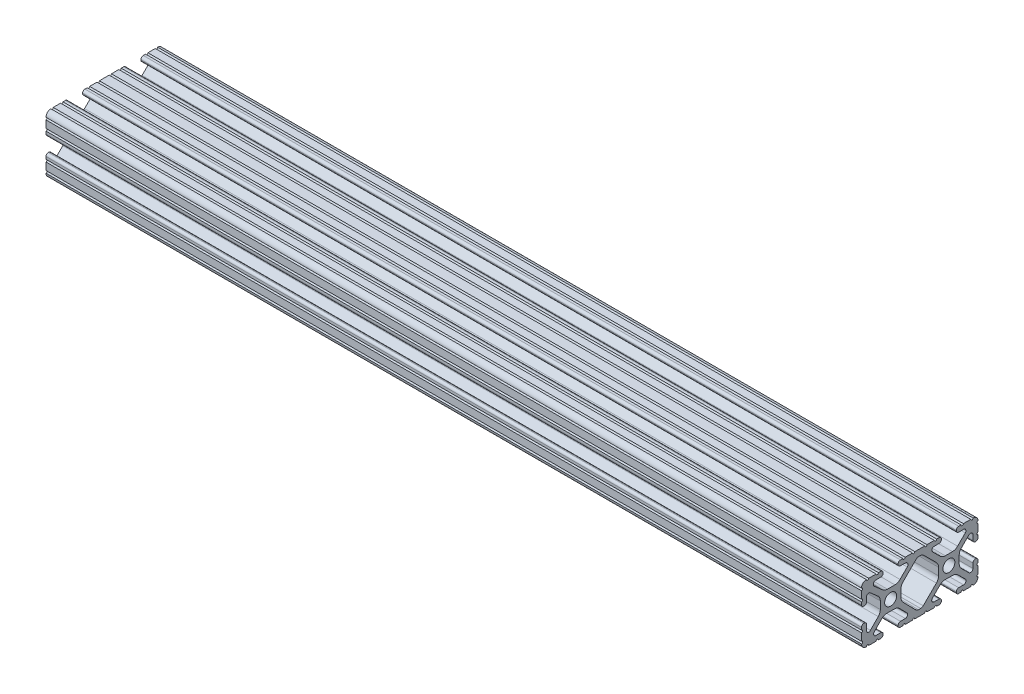
SolidWorks part; units mm, degrees
ref_plane "Front Plane" through (0, 0, 0) normal (0, 0, 1) x (1, 0, 0)
ref_plane "Top Plane" through (0, 0, 0) normal (0, 1, 0) x (1, 0, 0)
ref_plane "Right Plane" through (0, 0, 0) normal (1, 0, 0) x (0, 0, -1)
sketch "Sketch1" plane through (0, 0, 0) normal (0, 0, 1) x (1, 0, 0)
  line L0 (0, 0) -> (355.6, 0)
  dimension "D1" = 355.6
other "10 1020 PROFILE(1)"
ref_plane "Plane1" through (0, 0, 0) normal (1, 0, 0) x (0, 0, 1)
sketch "Sketch11" plane through (0, 0, 0) normal (1, 0, 0) x (0, 0, 1)
  line L1 (0, -12.7) -> (-25.4, -12.7) construction
  line L2 (0, -12.7) -> (0, 12.7) construction
  line L3 (0, 12.7) -> (-25.4, 12.7) construction
  line L4 (-25.4, -12.7) -> (-25.4, 12.7) construction
  line L5 (0, -12.7) -> (-25.4, 12.7) construction
  line L6 (0, 12.7) -> (-25.4, -12.7) construction
  line L7 (25.4, 12.7) -> (0, 12.7) construction
  line L8 (25.4, 12.7) -> (25.4, -12.7) construction
  line L9 (25.4, -12.7) -> (0, -12.7) construction
  line L10 (0, 12.7) -> (0, -12.7) construction
  line L11 (25.4, 12.7) -> (0, -12.7) construction
  line L12 (25.4, -12.7) -> (0, 12.7) construction
  line L17 (-8.1915, 1.6223) -> (-8.1915, -1.6223)
  line L18 (-1.504, 9.5765) -> (-7.252, 3.8768)
  line L19 (0.5515, 10.033) -> (-0.3952, 10.033)
  line L20 (7.2829, 3.8459) -> (1.6756, 9.5611)
  line L21 (8.1915, -1.6223) -> (8.1915, 1.6223)
  line L22 (1.5457, -9.5728) -> (7.2595, -3.8694)
  line L23 (-0.4332, -10.033) -> (0.4332, -10.033)
  line L24 (-7.2595, -3.8694) -> (-1.5457, -9.5728)
  line L136 (15.9385, 11.651) -> (15.9385, 11.5392)
  line L137 (16.9875, 10.4902) -> (19.1164, 10.4902)
  line L138 (19.8441, 8.7652) -> (16.619, 5.4551)
  line L139 (14.3449, 4.4958) -> (11.0833, 4.4958)
  line L140 (8.817, 5.4472) -> (5.5642, 8.7627)
  line L141 (6.2894, 10.4902) -> (8.4125, 10.4902)
  line L142 (9.4615, 11.5392) -> (9.4615, 11.651)
  line L143 (8.4125, 12.7) -> (7.3829, 12.7)
  line L144 (6.3669, 12.7) -> (3.1496, 12.7)
  line L145 (2.1336, 12.7) -> (-2.1336, 12.7)
  line L146 (-3.1496, 12.7) -> (-6.3669, 12.7)
  line L147 (-7.3829, 12.7) -> (-8.4125, 12.7)
  line L148 (-9.4615, 11.651) -> (-9.4615, 11.5392)
  line L149 (-8.4125, 10.4902) -> (-6.2836, 10.4902)
  line L150 (-5.5326, 8.6661) -> (-8.81, 5.4163)
  line L151 (-11.0455, 4.4958) -> (-14.3545, 4.4958)
  line L152 (-16.59, 5.4163) -> (-19.8674, 8.6661)
  line L153 (-19.1164, 10.4902) -> (-16.9875, 10.4902)
  line L154 (-15.9385, 11.5392) -> (-15.9385, 11.651)
  line L155 (-16.9875, 12.7) -> (-18.0171, 12.7)
  line L156 (-19.0331, 12.7) -> (-22.2504, 12.7)
  line L157 (-25.4, 9.5504) -> (-25.4, 6.3331)
  line L158 (-25.4, 5.3171) -> (-25.4, 4.2375)
  line L159 (-24.401, 3.2385) -> (-24.2392, 3.2385)
  line L160 (-23.1902, 4.2875) -> (-23.1902, 6.3347)
  line L161 (-21.434, 7.0665) -> (-18.148, 3.8082)
  line L162 (-17.2085, 1.5536) -> (-17.2085, -1.6952)
  line L163 (-18.1405, -3.9423) -> (-21.4316, -7.2274)
  line L164 (-23.1902, -6.498) -> (-23.1902, -4.2875)
  line L165 (-24.2392, -3.2385) -> (-24.351, -3.2385)
  line L166 (-25.4, -4.2875) -> (-25.4, -5.3171)
  line L167 (-25.4, -6.3331) -> (-25.4, -9.5504)
  line L168 (-22.2504, -12.7) -> (-19.0331, -12.7)
  line L169 (-18.0171, -12.7) -> (-16.9875, -12.7)
  line L170 (-15.9384, -11.651) -> (-15.9384, -11.5392)
  line L171 (-16.9875, -10.4902) -> (-19.1164, -10.4902)
  line L172 (-19.8341, -8.7551) -> (-16.4966, -5.4237)
  line L173 (-14.2536, -4.4958) -> (-11.1464, -4.4958)
  line L174 (-8.9034, -5.4237) -> (-5.5659, -8.7551)
  line L175 (-6.2836, -10.4902) -> (-8.4125, -10.4902)
  line L176 (-9.4616, -11.5392) -> (-9.4616, -11.651)
  line L177 (-8.4125, -12.7) -> (-7.3829, -12.7)
  line L178 (-6.3669, -12.7) -> (-3.1496, -12.7)
  line L179 (-2.1336, -12.7) -> (2.1336, -12.7)
  line L180 (3.1496, -12.7) -> (6.3669, -12.7)
  line L181 (7.3829, -12.7) -> (8.4125, -12.7)
  line L182 (9.4616, -11.651) -> (9.4616, -11.5392)
  line L183 (8.4125, -10.4902) -> (6.2894, -10.4902)
  line L184 (5.4807, -8.5353) -> (8.5979, -5.4237)
  line L185 (10.8409, -4.4958) -> (14.1026, -4.4958)
  line L186 (16.1879, -5.2766) -> (19.8682, -8.4822)
  line L187 (19.1164, -10.4902) -> (16.9875, -10.4902)
  line L188 (15.9384, -11.5392) -> (15.9384, -11.651)
  line L189 (16.9875, -12.7) -> (18.0171, -12.7)
  line L190 (19.0331, -12.7) -> (22.2504, -12.7)
  line L191 (25.4, -9.5504) -> (25.4, -6.3331)
  line L192 (25.4, -5.3171) -> (25.4, -4.2375)
  line L193 (24.401, -3.2385) -> (24.1892, -3.2385)
  line L194 (23.1902, -4.2375) -> (23.1902, -6.1559)
  line L195 (21.584, -6.8869) -> (18.2982, -4.025)
  line L196 (17.2085, -1.6308) -> (17.2085, 1.6308)
  line L197 (18.1094, 3.8465) -> (21.5263, 7.3534)
  line L198 (23.1902, 6.6769) -> (23.1902, 4.2375)
  line L199 (24.1892, 3.2385) -> (24.401, 3.2385)
  line L200 (25.4, 4.2375) -> (25.4, 5.3171)
  line L201 (25.4, 6.3332) -> (25.4, 9.5504)
  line L202 (22.2504, 12.7) -> (19.0331, 12.7)
  line L203 (18.0171, 12.7) -> (16.9875, 12.7)
  circle A1 centre (-12.7, 0) radius 2.6035
  circle A3 centre (12.7, 0) radius 2.6035
  arc A20 (-8.1915, -1.6223) -> (-7.2595, -3.8694) centre (-5.0165, -1.6223) ccw
  arc A21 (-7.252, 3.8768) -> (-8.1915, 1.6223) centre (-5.0165, 1.6223) ccw
  arc A22 (-0.3952, 10.033) -> (-1.504, 9.5765) centre (-0.3952, 8.4582) ccw
  arc A23 (1.6756, 9.5611) -> (0.5515, 10.033) centre (0.5515, 8.4582) ccw
  arc A24 (8.1915, 1.6223) -> (7.2829, 3.8459) centre (5.0165, 1.6223) ccw
  arc A25 (7.2595, -3.8694) -> (8.1915, -1.6223) centre (5.0165, -1.6223) ccw
  arc A26 (0.4332, -10.033) -> (1.5457, -9.5728) centre (0.4332, -8.4582) ccw
  arc A27 (-1.5457, -9.5728) -> (-0.4332, -10.033) centre (-0.4332, -8.4582) ccw
  arc A152 (16.9875, 12.7) -> (15.9385, 11.651) centre (16.9875, 11.651) ccw
  arc A153 (15.9385, 11.5392) -> (16.9875, 10.4902) centre (16.9875, 11.5392) ccw
  arc A154 (19.8441, 8.7652) -> (19.1164, 10.4902) centre (19.1164, 9.4742) ccw
  arc A155 (14.3449, 4.4958) -> (16.619, 5.4551) centre (14.3449, 7.6708) ccw
  arc A156 (8.817, 5.4472) -> (11.0833, 4.4958) centre (11.0833, 7.6708) ccw
  arc A157 (6.2894, 10.4902) -> (5.5642, 8.7627) centre (6.2894, 9.4742) ccw
  arc A158 (8.4125, 10.4902) -> (9.4615, 11.5392) centre (8.4125, 11.5392) ccw
  arc A159 (9.4615, 11.651) -> (8.4125, 12.7) centre (8.4125, 11.651) ccw
  arc A160 (6.3669, 12.7) -> (7.3829, 12.7) centre (6.8749, 12.7) ccw
  arc A161 (2.1336, 12.7) -> (3.1496, 12.7) centre (2.6416, 12.7) ccw
  arc A162 (-3.1496, 12.7) -> (-2.1336, 12.7) centre (-2.6416, 12.7) ccw
  arc A163 (-7.3829, 12.7) -> (-6.3669, 12.7) centre (-6.8749, 12.7) ccw
  arc A164 (-8.4125, 12.7) -> (-9.4615, 11.651) centre (-8.4125, 11.651) ccw
  arc A165 (-9.4615, 11.5392) -> (-8.4125, 10.4902) centre (-8.4125, 11.5392) ccw
  arc A166 (-5.5326, 8.6661) -> (-6.2836, 10.4902) centre (-6.2836, 9.4235) ccw
  arc A167 (-11.0455, 4.4958) -> (-8.81, 5.4163) centre (-11.0455, 7.6708) ccw
  arc A168 (-16.59, 5.4163) -> (-14.3545, 4.4958) centre (-14.3545, 7.6708) ccw
  arc A169 (-19.1164, 10.4902) -> (-19.8674, 8.6661) centre (-19.1164, 9.4235) ccw
  arc A170 (-16.9875, 10.4902) -> (-15.9385, 11.5392) centre (-16.9875, 11.5392) ccw
  arc A171 (-15.9385, 11.651) -> (-16.9875, 12.7) centre (-16.9875, 11.651) ccw
  arc A172 (-19.0331, 12.7) -> (-18.0171, 12.7) centre (-18.5251, 12.7) ccw
  arc A173 (-23.2664, 12.6998) -> (-22.2504, 12.7) centre (-22.7584, 12.7) ccw
  arc A174 (-23.2664, 12.6998) -> (-25.3998, 10.5664) centre (-23.2918, 10.5918) ccw
  arc A175 (-25.4, 9.5504) -> (-25.3998, 10.5664) centre (-25.4, 10.0584) ccw
  arc A176 (-25.4, 5.3171) -> (-25.4, 6.3331) centre (-25.4, 5.8251) ccw
  arc A177 (-25.4, 4.2375) -> (-24.401, 3.2385) centre (-24.401, 4.2375) ccw
  arc A178 (-24.2392, 3.2385) -> (-23.1902, 4.2875) centre (-24.2392, 4.2875) ccw
  arc A179 (-21.434, 7.0665) -> (-23.1902, 6.3347) centre (-22.1596, 6.3347) ccw
  arc A180 (-17.2085, 1.5536) -> (-18.148, 3.8082) centre (-20.3835, 1.5536) ccw
  arc A181 (-18.1405, -3.9423) -> (-17.2085, -1.6952) centre (-20.3835, -1.6952) ccw
  arc A182 (-23.1902, -6.498) -> (-21.4316, -7.2274) centre (-22.1596, -6.498) ccw
  arc A183 (-23.1902, -4.2875) -> (-24.2392, -3.2385) centre (-24.2392, -4.2875) ccw
  arc A184 (-24.351, -3.2385) -> (-25.4, -4.2875) centre (-24.351, -4.2875) ccw
  arc A185 (-25.4, -6.3331) -> (-25.4, -5.3171) centre (-25.4, -5.8251) ccw
  arc A186 (-25.3998, -10.5664) -> (-25.4, -9.5504) centre (-25.4, -10.0584) ccw
  arc A187 (-25.3998, -10.5664) -> (-23.2664, -12.6998) centre (-23.2918, -10.5918) ccw
  arc A188 (-22.2504, -12.7) -> (-23.2664, -12.6998) centre (-22.7584, -12.7) ccw
  arc A189 (-18.0171, -12.7) -> (-19.0331, -12.7) centre (-18.5251, -12.7) ccw
  arc A190 (-16.9875, -12.7) -> (-15.9384, -11.651) centre (-16.9875, -11.651) ccw
  arc A191 (-15.9384, -11.5392) -> (-16.9875, -10.4902) centre (-16.9875, -11.5392) ccw
  arc A192 (-19.8341, -8.7551) -> (-19.1164, -10.4902) centre (-19.1164, -9.4742) ccw
  arc A193 (-14.2536, -4.4958) -> (-16.4966, -5.4237) centre (-14.2536, -7.6708) ccw
  arc A194 (-8.9034, -5.4237) -> (-11.1464, -4.4958) centre (-11.1464, -7.6708) ccw
  arc A195 (-6.2836, -10.4902) -> (-5.5659, -8.7551) centre (-6.2836, -9.4742) ccw
  arc A196 (-8.4125, -10.4902) -> (-9.4616, -11.5392) centre (-8.4125, -11.5392) ccw
  arc A197 (-9.4616, -11.651) -> (-8.4125, -12.7) centre (-8.4125, -11.651) ccw
  arc A198 (-6.3669, -12.7) -> (-7.3829, -12.7) centre (-6.8749, -12.7) ccw
  arc A199 (-2.1336, -12.7) -> (-3.1496, -12.7) centre (-2.6416, -12.7) ccw
  arc A200 (3.1496, -12.7) -> (2.1336, -12.7) centre (2.6416, -12.7) ccw
  arc A201 (7.3829, -12.7) -> (6.3669, -12.7) centre (6.8749, -12.7) ccw
  arc A202 (8.4125, -12.7) -> (9.4616, -11.651) centre (8.4125, -11.651) ccw
  arc A203 (9.4616, -11.5392) -> (8.4125, -10.4902) centre (8.4125, -11.5392) ccw
  arc A204 (5.4807, -8.5353) -> (6.2894, -10.4902) centre (6.2894, -9.3455) ccw
  arc A205 (10.8409, -4.4958) -> (8.5979, -5.4237) centre (10.8409, -7.6708) ccw
  arc A206 (16.1879, -5.2766) -> (14.1026, -4.4958) centre (14.1026, -7.6708) ccw
  arc A207 (19.1164, -10.4902) -> (19.8682, -8.4822) centre (19.1164, -9.3455) ccw
  arc A208 (16.9875, -10.4902) -> (15.9384, -11.5392) centre (16.9875, -11.5392) ccw
  arc A209 (15.9384, -11.651) -> (16.9875, -12.7) centre (16.9875, -11.651) ccw
  arc A210 (19.0331, -12.7) -> (18.0171, -12.7) centre (18.5251, -12.7) ccw
  arc A211 (23.2664, -12.6998) -> (22.2504, -12.7) centre (22.7584, -12.7) ccw
  arc A212 (23.2664, -12.6998) -> (25.3998, -10.5664) centre (23.2918, -10.5918) ccw
  arc A213 (25.4, -9.5504) -> (25.3998, -10.5664) centre (25.4, -10.0584) ccw
  arc A214 (25.4, -5.3171) -> (25.4, -6.3331) centre (25.4, -5.8251) ccw
  arc A215 (25.4, -4.2375) -> (24.401, -3.2385) centre (24.401, -4.2375) ccw
  arc A216 (24.1892, -3.2385) -> (23.1902, -4.2375) centre (24.1892, -4.2375) ccw
  arc A217 (21.584, -6.8869) -> (23.1902, -6.1559) centre (22.2207, -6.1559) ccw
  arc A218 (17.2085, -1.6308) -> (18.2982, -4.025) centre (20.3835, -1.6308) ccw
  arc A219 (18.1094, 3.8465) -> (17.2085, 1.6308) centre (20.3835, 1.6308) ccw
  arc A220 (23.1902, 6.6769) -> (21.5263, 7.3534) centre (22.2207, 6.6769) ccw
  arc A221 (23.1902, 4.2375) -> (24.1892, 3.2385) centre (24.1892, 4.2375) ccw
  arc A222 (24.401, 3.2385) -> (25.4, 4.2375) centre (24.401, 4.2375) ccw
  arc A223 (25.4, 6.3332) -> (25.4, 5.3171) centre (25.4, 5.8251) ccw
  arc A224 (25.3998, 10.5664) -> (25.4, 9.5504) centre (25.4, 10.0584) ccw
  arc A225 (25.3998, 10.5664) -> (23.2664, 12.6998) centre (23.2918, 10.5918) ccw
  arc A226 (22.2504, 12.7) -> (23.2664, 12.6998) centre (22.7584, 12.7) ccw
  arc A227 (18.0171, 12.7) -> (19.0331, 12.7) centre (18.5251, 12.7) ccw
  point P3 (-12.7, 0)
  point P18 (0, 0)
  point P20 (0, 0)
  point P33 (12.7, 0)
  point P75 (12.7, -12.7)
  point P85 (25.4, 0)
  point P115 (12.7, 12.7)
  point P119 (-12.7, 12.7)
  point P122 (-25.4, 0)
  point P125 (-12.7, -12.7)
  point P128 (-25.4, -12.7)
  point P130 (-25.4, 12.7)
  point P133 (0, 12.7)
  point P137 (25.4, -12.7)
  point P140 (25.4, 12.7)
  point P143 (0, -12.7)
  dimension "D1" = 25.4
equation "\"D1@Sketch1\"=14in"
